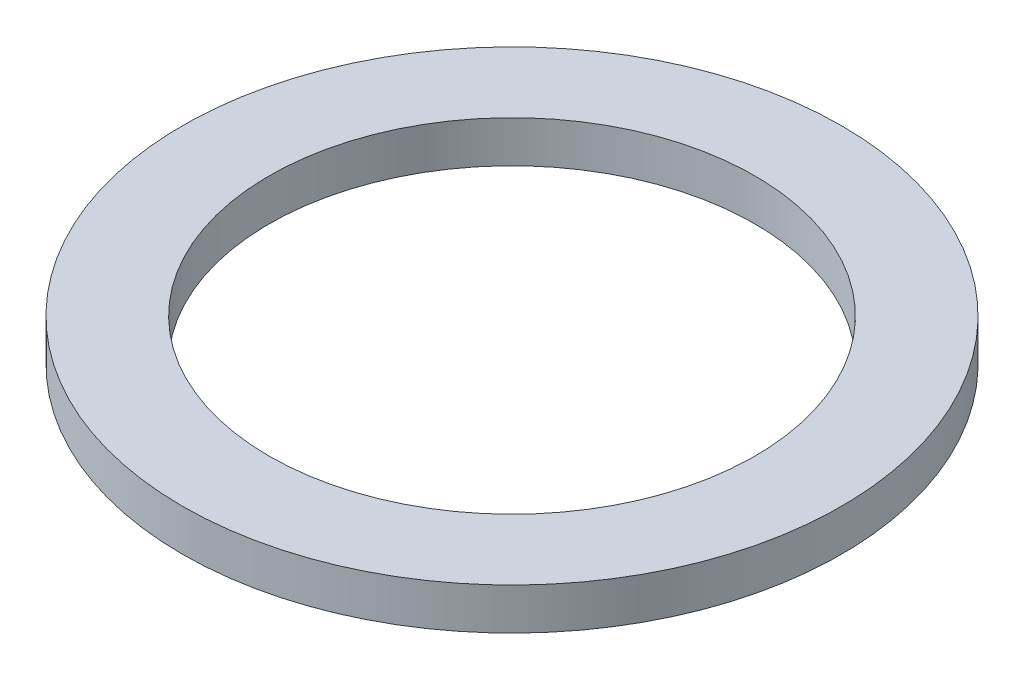
SolidWorks part; units mm, degrees
material "AISI 304"
ref_plane "前视基准面" through (0, 0, 0) normal (0, 0, 1) x (1, 0, 0)
ref_plane "上视基准面" through (0, 0, 0) normal (0, 1, 0) x (1, 0, 0)
ref_plane "右视基准面" through (0, 0, 0) normal (1, 0, 0) x (0, 0, -1)
other "Configuration Table"
sketch "草图1" plane through (0, 0, 0) normal (0, 1, 0) x (1, 0, 0)
  circle A0 centre (0, 0) radius 35
  circle A1 centre (0, 0) radius 47.5
  dimension "D1" = 70
  dimension "D2" = 95
extrude "凸台-拉伸1" add sketch "草图1" along normal blind 6
